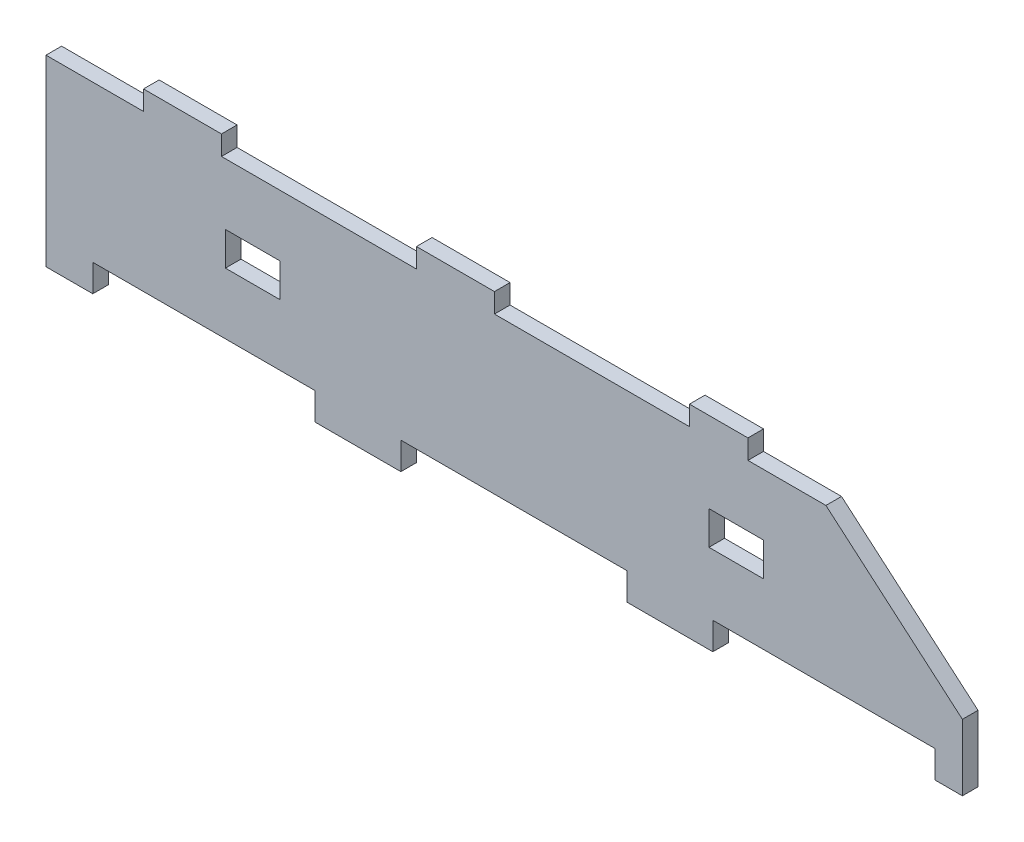
SolidWorks part; units mm, degrees
ref_plane "Front Plane" through (0, 0, 0) normal (0, 0, 1) x (1, 0, 0)
ref_plane "Top Plane" through (0, 0, 0) normal (0, 1, 0) x (1, 0, 0)
ref_plane "Right Plane" through (0, 0, 0) normal (1, 0, 0) x (0, 0, -1)
sketch "Sketch1" plane through (0, 0, 0) normal (0, 0, 1) x (1, 0, 0)
  line L2 (-105.5, 0) -> (-48.5, 0)
  line L4 (-117.5, 0) -> (-117.5, 40)
  line L6 (117.5, 0) -> (117.5, 10)
  line L7 (117.5, 10) -> (82.5, 40)
  line L8 (110.5, 0) -> (110.5, -7)
  line L9 (110.5, -7) -> (117.5, -7)
  line L10 (117.5, -7) -> (117.5, 0)
  line L11 (-26.5, 0) -> (31.5, 0)
  line L12 (53.5, 0) -> (53.5, -7)
  line L13 (53.5, -7) -> (31.5, -7)
  line L14 (31.5, -7) -> (31.5, 0)
  line L16 (53.5, 0) -> (110.5, 0)
  line L17 (-26.5, 0) -> (-26.5, -7)
  line L18 (-26.5, -7) -> (-48.5, -7)
  line L19 (-48.5, -7) -> (-48.5, 0)
  line L22 (-105.5, 0) -> (-105.5, -7)
  line L23 (-105.5, -7) -> (-117.5, -7)
  line L24 (-117.5, -7) -> (-117.5, 0)
  line L25 (-117.5, 40) -> (-92.5, 40)
  line L26 (-92.5, 40) -> (-92.5, 45)
  line L27 (-92.5, 45) -> (-72.5, 45)
  line L28 (-72.5, 45) -> (-72.5, 40)
  line L29 (-72.5, 40) -> (-22.5, 40)
  line L30 (-22.5, 40) -> (-22.5, 45)
  line L31 (-22.5, 45) -> (-2.5, 45)
  line L32 (-2.5, 45) -> (-2.5, 40)
  line L33 (-2.5, 40) -> (47.5, 40)
  line L34 (47.5, 40) -> (47.5, 45)
  line L35 (47.5, 45) -> (62.5, 45)
  line L36 (62.5, 45) -> (62.5, 40)
  line L37 (62.5, 40) -> (82.5, 40)
  dimension "D2" = 200
  dimension "D3" = 25
  dimension "D4" = 5
  dimension "D5" = 40
  dimension "D6" = 10
  dimension "D7" = 7
  dimension "D8" = 7
  dimension "D9" = 7
  dimension "D10" = 57
  dimension "D11" = 7
  dimension "D12" = 22
  dimension "D13" = 58
  dimension "D14" = 7
  dimension "D15" = 22
  dimension "D16" = 12
  dimension "D17" = 7
  dimension "D18" = 12
  dimension "D19" = 20
  dimension "D20" = 5
  dimension "D21" = 50
  dimension "D22" = 5
  dimension "D23" = 20
  dimension "D24" = 5
  dimension "D25" = 50
  dimension "D26" = 5
  dimension "D27" = 15
  dimension "D28" = 5
extrude "Boss-Extrude2" add sketch "Sketch1" along normal blind 4 contours L23 L24 L4 L25 L26 L27 L28 L29 L30 L31 L32 L33 L34 L35 L36 L37 L7 L6 L10 L9 L8 L16 L12 L13 L14 L11 L17 L18 L19 L2 L22
sketch "Sketch2" plane through (0, 0, 4) normal (0, 0, 1) x (1, 0, 0)
  line L8 (-71.5, 20) -> (-71.5, 24.3)
  line L9 (-71.5, 24.3) -> (-57.5, 24.3)
  line L10 (-57.5, 24.3) -> (-57.5, 15.7)
  line L11 (-57.5, 15.7) -> (-71.5, 15.7)
  line L12 (-71.5, 15.7) -> (-71.5, 20)
  line L14 (52.5, 20) -> (52.5, 24.3)
  line L15 (52.5, 24.3) -> (66.5, 24.3)
  line L16 (66.5, 24.3) -> (66.5, 15.7)
  line L17 (66.5, 15.7) -> (52.5, 15.7)
  line L18 (52.5, 15.7) -> (52.5, 20)
  dimension "D2" = 4.3
  dimension "D3" = 14
  dimension "D4" = 8.6
  dimension "D6" = 4.3
  dimension "D7" = 14
  dimension "D8" = 8.6
  dimension "D9" = 14
extrude "Cut-Extrude1" cut sketch "Sketch2" against normal up to surface (4 mm away) up to face at (-1.6379, 18.7586, 0)
